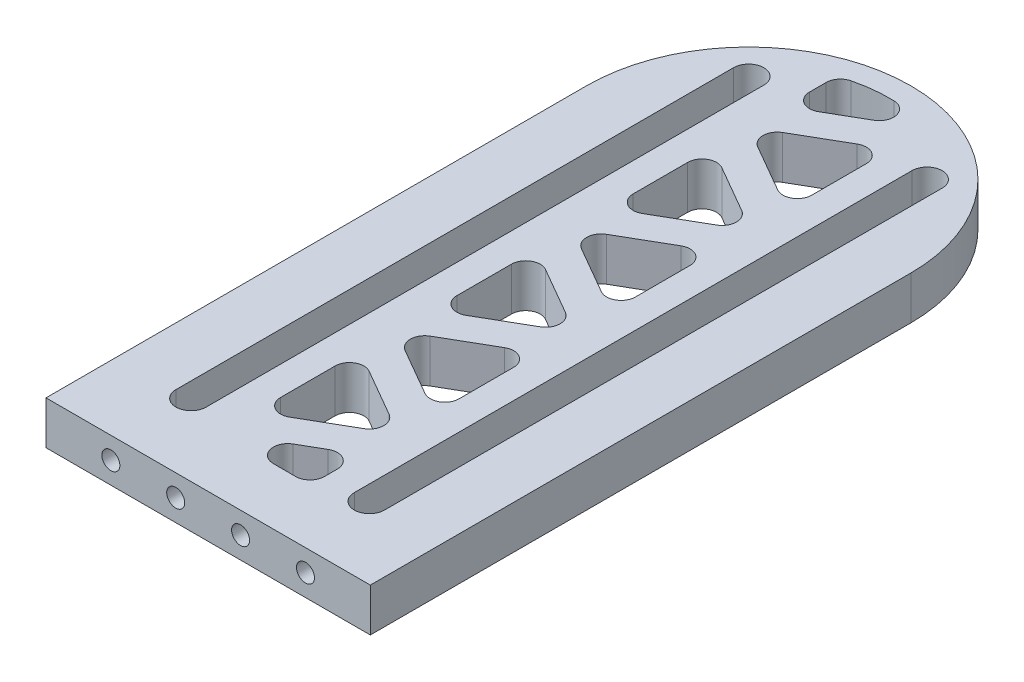
SolidWorks part; units mm, degrees
material "Сплав 2024"
ref_plane "Спереди" through (0, 0, 0) normal (0, 0, 1) x (1, 0, 0)
ref_plane "Сверху" through (0, 0, 0) normal (0, 1, 0) x (1, 0, 0)
ref_plane "Справа" through (0, 0, 0) normal (1, 0, 0) x (0, 0, -1)
sketch "Эскиз1" plane through (0, 0, 0) normal (0, 1, 0) x (1, 0, 0)
  line L2 (-15.9099, 15.9099) -> (15.9099, -15.9099) construction
  line L3 (15.9099, 15.9099) -> (-15.9099, -15.9099) construction
  line L4 (-22.5, 0) -> (-22.5, -75)
  line L5 (-22.5, -75) -> (22.5, -75)
  line L6 (22.5, 0) -> (22.5, -75)
  arc A0 (22.5, 0) -> (-22.5, 0) centre (0, 0) ccw
  dimension "D1" = 45
  dimension "D2" = 75
  dimension "D3" = 45
extrude "Бобышка-Вытянуть1" add sketch "Эскиз1" along normal blind 6
sketch "Эскиз2" plane through (0, 6, 0) normal (0, 1, 0) x (1, 0, 0)
  line L0 (-12.3744, -12.3744) -> (12.3744, 12.3744) construction
  line L1 (-36.6046, 36.6046) -> (36.6046, -36.6046) construction
  line L2 (22.5, -75) -> (22.5, 0) construction
  line L3 (-12.3744, 28.2466) -> (-12.3744, -50.5484) construction
  line L4 (12.3744, 23.4168) -> (12.3744, -56.6851) construction
  line L5 (-12.3744, 12.3744) -> (-12.3744, -65) construction
  line L6 (-10.2744, 12.3744) -> (-10.2744, -65)
  line L7 (-14.4744, 12.3744) -> (-14.4744, -65)
  line L8 (-22.5, -75) -> (22.5, -75) construction
  line L9 (0, 10.4779) -> (0, -10.8682) construction
  line L10 (12.3744, 12.3744) -> (12.3744, -65) construction
  line L11 (10.2744, 12.3744) -> (10.2744, -65)
  line L12 (14.4744, 12.3744) -> (14.4744, -65)
  circle A0 centre (0, 0) radius 6 construction
  circle A1 centre (0, 0) radius 17.5 construction
  arc A2 (-10.2744, 12.3744) -> (-14.4744, 12.3744) centre (-12.3744, 12.3744) ccw
  arc A3 (-14.4744, -65) -> (-10.2744, -65) centre (-12.3744, -65) ccw
  arc A4 (10.2744, 12.3744) -> (14.4744, 12.3744) centre (12.3744, 12.3744) cw
  arc A5 (14.4744, -65) -> (10.2744, -65) centre (12.3744, -65) cw
  point P12 (-12.3744, 12.3744)
  point P13 (12.3744, 12.3744)
  point P18 (-12.3744, -26.3128)
  point P28 (12.3744, -26.3128)
  dimension "D1" = 12
  dimension "D2" = 35
  dimension "D4" = 2.1
  dimension "D3" = 45
  dimension "D5" = 10
hole_wizard "Цековка для  винта с полукруглой головкой M31" [suppressed] positions "Эскиз4" profile "Эскиз5" counterbore size "M3" standard "Ansi Metric"
sketch "Эскиз4" plane through (0, 6, 0) normal (0, 1, 0) x (1, 0, 0)
  line L2 (-36.6046, 36.6046) -> (36.6046, -36.6046) construction
  line L3 (-12.3744, -12.3744) -> (12.3744, 12.3744) construction
  circle A0 centre (0, 0) radius 6 construction
  point P0 (-4.2426, 4.2426)
  point P6 (-4.2426, -4.2426)
  point P10 (4.2426, -4.2426)
  point P12 (4.2426, 4.2426)
sketch "Эскиз5" plane through (-4.2426, 6, -4.2426) normal (1, 0, 0) x (0, 0, 1)
  line L0 (0, 0) -> (0, 6)
  line L1 (0, 6) -> (1.7, 6)
  line L3 (1.7, 6) -> (1.7, 2)
  line L4 (1.7, 2) -> (3.35, 2)
  line L5 (3.35, 2) -> (3.35, 0)
  line L7 (3.35, 0) -> (0, 0)
  line L11 (0, -6.35) -> (0, 107.95) construction
  dimension "Диаметр сквозного отверстия" = 3.4
  dimension "Глубина сквозного отверстия" = 6
  dimension "Диаметр цековки" = 6.7
  dimension "Глубина цековки" = 2
hole_wizard "Отверстие обработанное метчиком M4x0.71" [suppressed] positions "Эскиз7" profile "Эскиз6" tap size "M4x0.7" standard "Ansi Metric"
sketch "Эскиз7" [suppressed] plane through (0, 4, 0) normal (0, 1, 0) x (1, 0, 0)
  line L0 (22.5, 0) -> (-22.5, 0) construction
  line L1 (0, 22.5) -> (0, -22.5) construction
  circle A0 centre (0, 0) radius 19.25 construction
  point P0 (-19.25, 0)
  point P6 (0, -19.25)
  point P10 (19.25, 0)
  point P12 (0, 19.25)
sketch "Эскиз6" plane through (-19.25, 4, 0) normal (1, 0, 0) x (0, 0, 1)
  line L0 (0, 0) -> (0, 4)
  line L1 (0, 4) -> (1.65, 4)
  line L2 (1.65, 4) -> (1.65, 0)
  line L5 (1.65, 0) -> (0, 0)
  line L11 (0, -6.35) -> (0, 107.95) construction
  dimension "Диаметр резьбы" = 3.3
  dimension "Глубина проходного сверла" = 4
extrude "Вырез-Вытянуть1" cut sketch "Эскиз2" against normal through all
sketch "Эскиз8" plane through (0, 0, 75) normal (0, 0, 1) x (1, 0, 0)
  line L0 (-22.5, 3) -> (22.5, 3) construction
  line L1 (-22.5, 6) -> (-22.5, 0) construction
  line L2 (22.5, 6) -> (22.5, 0) construction
  line L3 (-13.5, 6) -> (-13.5, 0) construction
  line L4 (-22.5, 6) -> (22.5, 6) construction
  line L5 (-22.5, 0) -> (22.5, 0) construction
  line L6 (-4.5, 6) -> (-4.5, 0) construction
  line L7 (4.5, 6) -> (4.5, 0) construction
  line L8 (13.5, 6) -> (13.5, 0) construction
  line L9 (-22.5, 0) -> (22.5, 0) construction
  dimension "D1" = 9
  dimension "D2" = 9
  dimension "D3" = 9
  dimension "D4" = 9
sketch "Эскиз11" plane through (0, 6, 0) normal (0, 1, 0) x (1, 0, 0)
  line L0 (-6.2744, -75) -> (-6.2744, 21.6075) construction
  line L1 (-22.5, -75) -> (22.5, -75) construction
  line L2 (6.2744, 21.6075) -> (6.2744, -75) construction
  line L3 (-10.2744, -65) -> (-10.2744, 12.3744) construction
  line L4 (10.2744, 12.3744) -> (10.2744, -65) construction
  line L5 (-17.2262, 14.4744) -> (17.2262, 14.4744) construction
  line L6 (-22.5, -67.1) -> (22.5, -67.1) construction
  line L7 (-22.5, 0) -> (-22.5, -75) construction
  line L8 (22.5, -75) -> (22.5, 0) construction
  line L10 (6.2744, 18.5) -> (-6.2744, 11.255)
  line L11 (-6.2744, 11.255) -> (-6.2744, 18.5)
  line L12 (-6.2744, 6.2667) -> (6.2744, 13.5117)
  line L13 (6.2744, 13.5117) -> (6.2744, -0.9783)
  line L14 (6.2744, -0.9783) -> (-6.2744, 6.2667)
  line L15 (-6.2744, 1.2784) -> (6.2744, -5.9666)
  line L16 (6.2744, -5.9666) -> (-6.2744, -13.2117)
  line L17 (-6.2744, -13.2117) -> (-6.2744, 1.2784)
  line L18 (-6.2744, -18.2) -> (6.2744, -10.955)
  line L19 (6.2744, -10.955) -> (6.2744, -25.445)
  line L20 (6.2744, -25.445) -> (-6.2744, -18.2)
  line L21 (-6.2744, -23.1883) -> (6.2744, -30.4333)
  line L22 (6.2744, -30.4333) -> (-6.2744, -37.6783)
  line L23 (-6.2744, -37.6783) -> (-6.2744, -23.1883)
  line L24 (-6.2744, -42.6666) -> (6.2744, -35.4216)
  line L25 (6.2744, -35.4216) -> (6.2744, -49.9116)
  line L26 (6.2744, -49.9116) -> (-6.2744, -42.6666)
  line L27 (-6.2744, -47.6549) -> (6.2744, -54.8999)
  line L28 (6.2744, -54.8999) -> (-6.2744, -62.145)
  line L29 (-6.2744, -62.145) -> (-6.2744, -47.6549)
  line L30 (-6.2744, -67.1333) -> (6.2744, -67.1333)
  line L31 (6.2744, -67.1333) -> (6.2744, -59.8882)
  line L32 (6.2744, -59.8882) -> (-6.2744, -67.1333)
  line L33 (-12.8062, 18.5) -> (12.8062, 18.5) construction
  arc A0 (22.5, 0) -> (-22.5, 0) centre (0, 0) ccw construction
  arc A1 (-10.2744, 12.3744) -> (-14.4744, 12.3744) centre (-12.3744, 12.3744) ccw construction
  arc A2 (-6.2744, 18.5) -> (6.2744, 18.5) centre (0, 0) cw
  arc A3 (-14.4744, -65) -> (-10.2744, -65) centre (-12.3744, -65) ccw construction
  point P53 (0, 22.5)
  dimension "D3" = 4.32
  dimension "D1" = 4
  dimension "D2" = 4
  dimension "D4" = 60
  dimension "D5" = 60
  dimension "D6" = 60
  dimension "D7" = 60
  dimension "D8" = 60
  dimension "D9" = 60
  dimension "D10" = 4.32
  dimension "D11" = 4.32
  dimension "D12" = 4.32
  dimension "D13" = 4.32
  dimension "D14" = 4.32
  dimension "D15" = 4.32
  dimension "D16" = 4
  dimension "D17" = 30
extrude "Вырез-Вытянуть2" cut sketch "Эскиз11" against normal through all
fillet "Скругление1" radius 2 24 edges at (6.2744, 3, 67.1333) (-6.2744, 3, 67.1333) (6.2744, 3, 59.8882) (-6.2744, 3, 62.145) (6.2744, 3, 54.8999) (-6.2744, 3, 47.6549) (-6.2744, 3, 42.6666) (6.2744, 3, 35.4216) (6.2744, 3, 49.9116) (6.2744, 3, 25.445) (6.2744, 3, 10.955) (6.2744, 3, 30.4333) (-6.2744, 3, 23.1883) (-6.2744, 3, 37.6783) (-6.2744, 3, 18.2) (-6.2744, 3, 13.2117) (6.2744, 3, 5.9666) (-6.2744, 3, -1.2784) (-6.2744, 3, -6.2667) (6.2744, 3, 0.9783) (6.2744, 3, -18.5) (-6.2744, 3, -18.5) (-6.2744, 3, -11.255) (6.2744, 3, -13.5117)
hole_wizard "Отверстие обработанное метчиком M3x0.51" positions "Эскиз10" profile "Эскиз9" tap size "M3x0.5" standard "Ansi Metric"
sketch "Эскиз10" plane through (0, 0, 75) normal (0, 0, 1) x (1, 0, 0)
  line L0 (-13.5, 6) -> (-13.5, 0) construction
  line L1 (-4.5, 6) -> (-4.5, 0) construction
  line L2 (4.5, 6) -> (4.5, 0) construction
  line L3 (13.5, 6) -> (13.5, 0) construction
  point P0 (-13.5, 3)
  point P4 (-4.5, 3)
  point P8 (4.5, 3)
  point P12 (13.5, 3)
sketch "Эскиз9" plane through (-13.5, 3, 75) normal (1, 0, 0) x (0, -1, 0)
  line L0 (0, 0) -> (0, 9.2511)
  line L1 (0, 9.2511) -> (1.25, 8.5)
  line L2 (1.25, 8.5) -> (1.25, 0)
  line L5 (1.25, 0) -> (0, 0)
  line L10 (0, 9.2511) -> (-1.25, 8.5) construction
  line L11 (0, -6.35) -> (0, 107.95) construction
  dimension "Диаметр сверла" = 2.5
  dimension "Глубина сверла" = 8.5
  dimension "Угол заточки сверла" = 118
cosmetic thread "Отверстие резьбы1" parameters "D1"=6, "D2"=3
cosmetic thread "Отверстие резьбы2" parameters "D1"=6, "D2"=3
cosmetic thread "Отверстие резьбы4" parameters "D1"=6, "D2"=3
cosmetic thread "Отверстие резьбы5" parameters "D1"=6, "D2"=3
equation "\"D1@Эскиз8\"=\"D1@Эскиз1\"/5"
equation "\"D2@Эскиз8\"=\"D1@Эскиз8\""
equation "\"D3@Эскиз8\"=\"D1@Эскиз8\""
equation "\"D4@Эскиз8\"=\"D1@Эскиз8\""
equation "\"D4@Эскиз11\"=60"
equation "\"D5@Эскиз11\"=\"D4@Эскиз11\""
equation "\"D6@Эскиз11\"=\"D4@Эскиз11\""
equation "\"D7@Эскиз11\"=\"D4@Эскиз11\""
equation "\"D8@Эскиз11\"=\"D4@Эскиз11\""
equation "\"D9@Эскиз11\"=\"D4@Эскиз11\""
equation "\"D17@Эскиз11\"=\"D4@Эскиз11\"/2"
equation "\"D11@Эскиз11\"=\"D10@Эскиз11\""
equation "\"D12@Эскиз11\"=\"D10@Эскиз11\""
equation "\"D13@Эскиз11\"=\"D10@Эскиз11\""
equation "\"D14@Эскиз11\"=\"D10@Эскиз11\""
equation "\"D15@Эскиз11\"=\"D10@Эскиз11\""
equation "\"D3@Эскиз11\"=\"D10@Эскиз11\""
